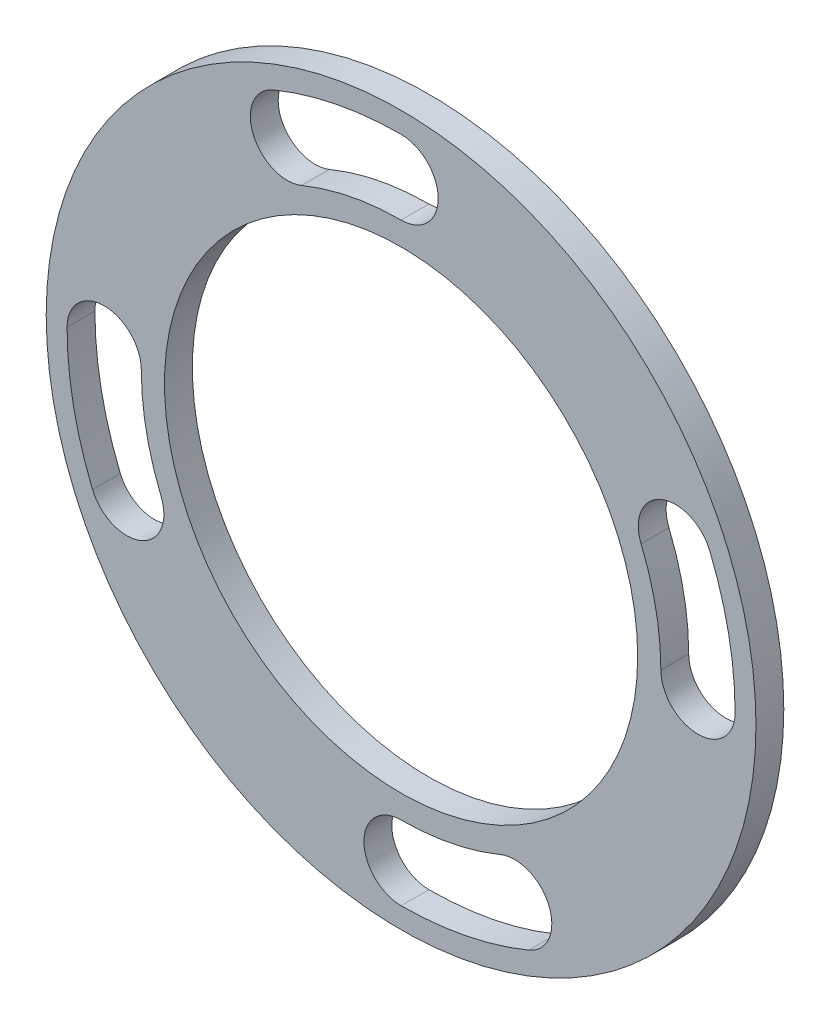
SolidWorks part; units mm, degrees
ref_plane "Front Plane" through (0, 0, 0) normal (0, 0, 1) x (1, 0, 0)
ref_plane "Top Plane" through (0, 0, 0) normal (0, 1, 0) x (1, 0, 0)
ref_plane "Right Plane" through (0, 0, 0) normal (1, 0, 0) x (0, 0, -1)
sketch "Sketch1" plane through (0, 0, 0) normal (0, 0, 1) x (1, 0, 0)
  circle A0 centre (0, 0) radius 7.65
  circle A1 centre (0, 0) radius 5.1
  arc A2 (0, 5.6) -> (0, 7.2) centre (0, 6.4) ccw
  arc A5 (6.6519, 2.7553) -> (5.1737, 2.143) centre (5.9128, 2.4492) ccw
  arc A6 (5.6, 0) -> (7.2, 0) centre (6.4, 0) ccw
  arc A9 (2.7553, -6.6519) -> (2.143, -5.1737) centre (2.4492, -5.9128) ccw
  arc A10 (0, -5.6) -> (0, -7.2) centre (0, -6.4) ccw
  arc A13 (-6.6519, -2.7553) -> (-5.1737, -2.143) centre (-5.9128, -2.4492) ccw
  arc A14 (-5.6, 0) -> (-7.2, 0) centre (-6.4, 0) ccw
  arc A17 (-2.7553, 6.6519) -> (-2.143, 5.1737) centre (-2.4492, 5.9128) ccw
  circle A18 centre (-5.9128, 2.4492) radius 0.8 [skipped]
  circle A19 centre (-4.5255, 4.5255) radius 0.8 [skipped]
  circle A20 centre (2.4492, 5.9128) radius 0.8 [skipped]
  circle A21 centre (4.5255, 4.5255) radius 0.8 [skipped]
  circle A22 centre (5.9128, -2.4492) radius 0.8 [skipped]
  circle A23 centre (4.5255, -4.5255) radius 0.8 [skipped]
  circle A24 centre (-2.4492, -5.9128) radius 0.8 [skipped]
  circle A25 centre (-4.5255, -4.5255) radius 0.8 [skipped]
  arc A26 (0, 7.2) -> (-2.7553, 6.6519) centre (0, 0) ccw
  arc A27 (0, 5.6) -> (-2.143, 5.1737) centre (0, 0) ccw
  arc A28 (-7.2, 0) -> (-6.6519, -2.7553) centre (0, 0) ccw
  arc A29 (-5.6, 0) -> (-5.1737, -2.143) centre (0, 0) ccw
  arc A30 (0, -5.6) -> (2.143, -5.1737) centre (0, 0) ccw
  arc A31 (0, -7.2) -> (2.7553, -6.6519) centre (0, 0) ccw
  arc A32 (5.6, 0) -> (5.1737, 2.143) centre (0, 0) ccw
  arc A33 (7.2, 0) -> (6.6519, 2.7553) centre (0, 0) ccw
  point P15 (0, 0)
  dimension "D1" = 6.4
  dimension "D3" = 15.3
  dimension "D4" = 10.2
  dimension "D5" = 1.6
  dimension "D2" = 16
extrude "Boss-Extrude1" add sketch "Sketch1" along normal blind 0.6
